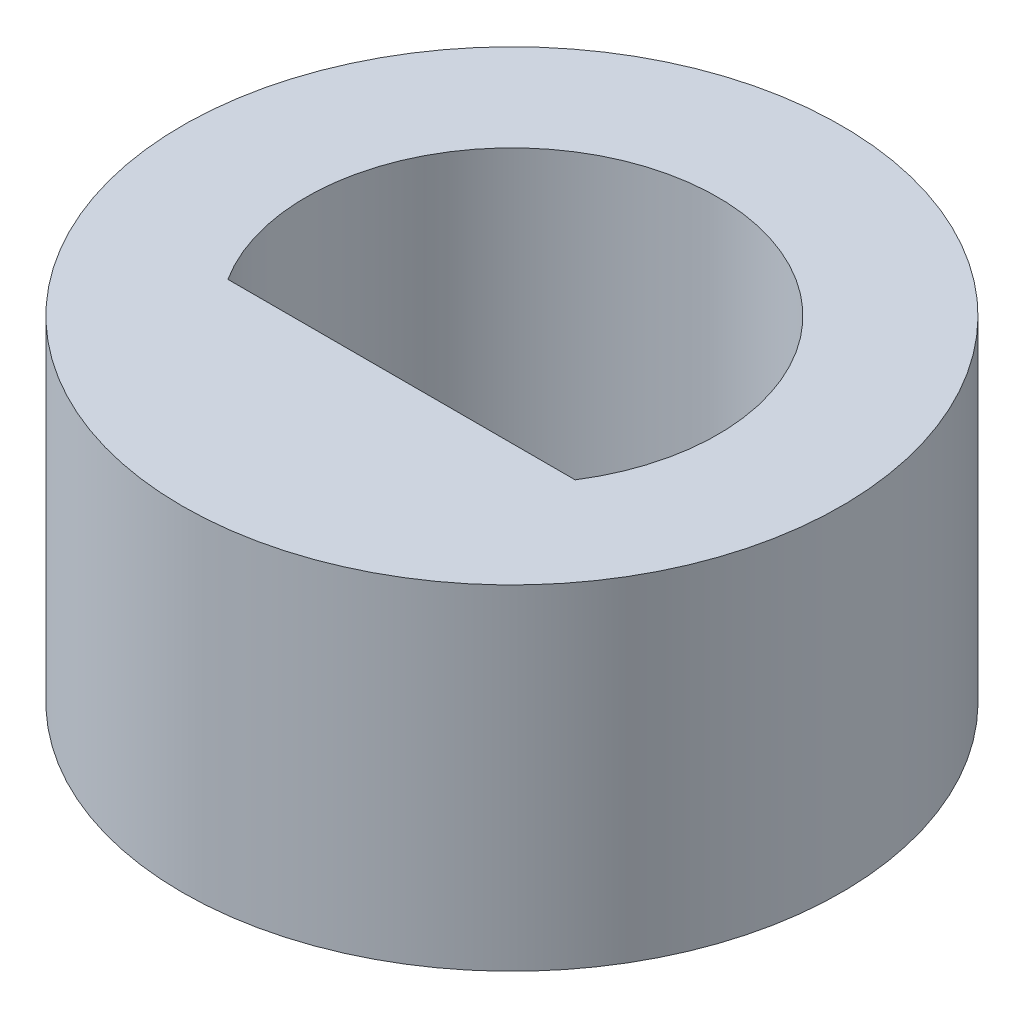
SolidWorks part; units mm, degrees
ref_plane "Front Plane" through (0, 0, 0) normal (0, 0, 1) x (1, 0, 0)
ref_plane "Top Plane" through (0, 0, 0) normal (0, 1, 0) x (1, 0, 0)
ref_plane "Right Plane" through (0, 0, 0) normal (1, 0, 0) x (0, 0, -1)
sketch "Sketch1" plane through (0, 0, 0) normal (0, 1, 0) x (1, 0, 0)
  line L2 (-2.5948, -1.65) -> (2.5948, -1.65)
  arc A0 (2.5948, -1.65) -> (-2.5948, -1.65) centre (0, 0) ccw
  circle A2 centre (0, 0) radius 4.925
  point P5 (0, 0)
  dimension "D1" = 6.15
  dimension "D2" = 9.85
  dimension "D3" = 1.65
extrude "Boss-Extrude1" add sketch "Sketch1" along normal blind 5
